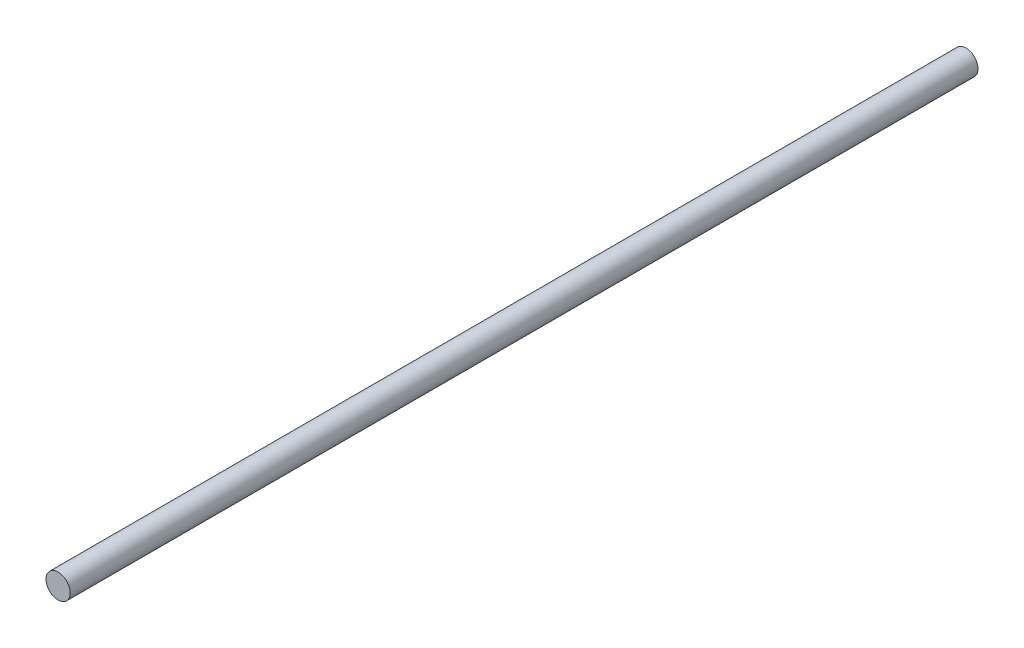
SolidWorks part; units mm, degrees
material "AISI 1020 Steel, Cold Rolled"
ref_plane "Front Plane" through (0, 0, 0) normal (0, 0, 1) x (1, 0, 0)
ref_plane "Top Plane" through (0, 0, 0) normal (0, 1, 0) x (1, 0, 0)
ref_plane "Right Plane" through (0, 0, 0) normal (1, 0, 0) x (0, 0, -1)
sketch "Sketch1" plane through (0, 0, 0) normal (0, 0, 1) x (1, 0, 0)
  circle A0 centre (0, 0) radius 8
  dimension "D1" = 16
extrude "Boss-Extrude1" add sketch "Sketch1" along normal blind 600
ref_plane "Плоскость1" through (0, 0, 0) normal (1, 0, 0) x (0, 0, -1)
equation "\"SBR16.Length.X\"= 600мм"
equation "\"SBR16.Length.Y\"= 500мм"
equation "\"SBR16.Length.Z\"= 250мм"
equation "\"D1@Boss-Extrude1\"= \"SBR16.Length.X\""
